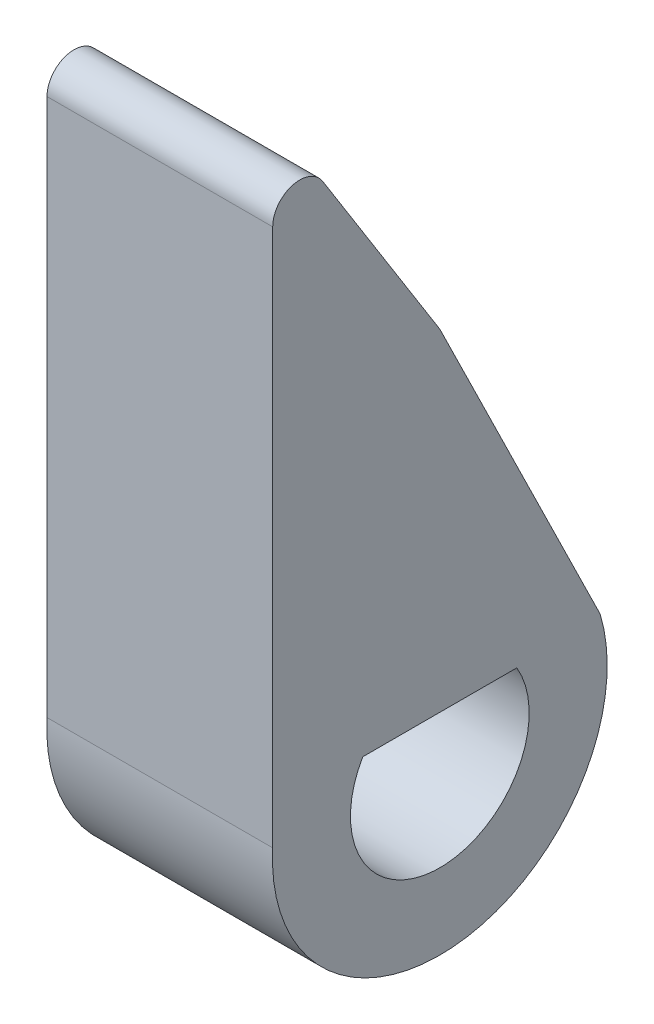
SolidWorks part; units mm, degrees
ref_plane "Front Plane" through (0, 0, 0) normal (0, 0, 1) x (1, 0, 0)
ref_plane "Top Plane" through (0, 0, 0) normal (0, 1, 0) x (1, 0, 0)
ref_plane "Right Plane" through (0, 0, 0) normal (1, 0, 0) x (0, 0, -1)
sketch "Sketch3" plane through (0, 0, 0) normal (1, 0, 0) x (0, 0, -1)
  line L2 (-54.6708, 30.9688) -> (-55.4472, 28.071)
  line L3 (-52.6708, 30.9688) -> (-51.8943, 28.071)
  arc A0 (-52.6708, 30.9688) -> (-54.6708, 30.9688) centre (-53.6708, 30.6404) ccw
  arc A1 (-55.4472, 28.071) -> (-51.8943, 28.071) centre (-53.6708, 27.5404) ccw
  dimension "D1" = 3.1
  dimension "D3" = 3
  dimension "D4" = 3
  dimension "D5" = 0
extrude "Boss-Extrude2" add sketch "Sketch3" along normal blind 2.5
sketch "Sketch4" plane through (2.5, 0, 0) normal (1, 0, 0) x (0, 0, -1)
  circle A0 centre (-53.6708, 27.5142) radius 0.99
  dimension "D1" = 1.98
extrude "Cut-Extrude2" cut sketch "Sketch4" against normal through all
sketch "Sketch7" plane through (2.5, 0, 0) normal (1, 0, 0) x (0, 0, -1)
  line L1 (-54.6674, 28.0164) -> (-52.6476, 28.0164)
  line L2 (-54.6674, 28.0164) -> (-54.6674, 28.8013)
  line L3 (-54.6674, 28.8013) -> (-52.6476, 28.8013)
  line L4 (-52.6476, 28.0164) -> (-52.6476, 28.8013)
extrude "Boss-Extrude5" add sketch "Sketch7" against normal up to surface (2.5 mm away) up to face at (0, 27.5142, 52.6808)
fillet "Fillet1" radius 0.2 2 edges at (0, 26.5242, 53.6708) (0, 28.0164, 53.6708)
sketch "Sketch8" plane through (2.5, 0, 0) normal (1, 0, 0) x (0, 0, -1)
  line L0 (-55.522, 27.6417) -> (-55.522, 34.6417)
  line L3 (-55.522, 34.6417) -> (-53.6708, 31.693)
  line L4 (-53.6708, 31.693) -> (-55.522, 27.6417)
  arc A0 (-55.4472, 28.071) -> (-51.8943, 28.071) centre (-53.6708, 27.5404) ccw construction
  arc A2 (-52.6708, 30.9688) -> (-54.6708, 30.9688) centre (-53.6708, 30.6404) ccw construction
  dimension "D1" = 7
extrude "Boss-Extrude6" add sketch "Sketch8" against normal up to surface (2.5 mm away) up to face at (0, 27.2703, 53.6708)
sketch "Sketch12" plane through (2.5, 0, 0) normal (1, 0, 0) x (0, 0, -1)
  line L0 (-53.6708, 31.693) -> (-51.8943, 28.071)
  line L1 (-51.8943, 28.071) -> (-51.7816, 31.693)
  line L2 (-51.7816, 31.693) -> (-53.6708, 31.693)
extrude "Cut-Extrude5" cut sketch "Sketch12" against normal through all
fillet "Fillet14" radius 0.3 1 edges at (1.25, 34.6417, 55.522)
